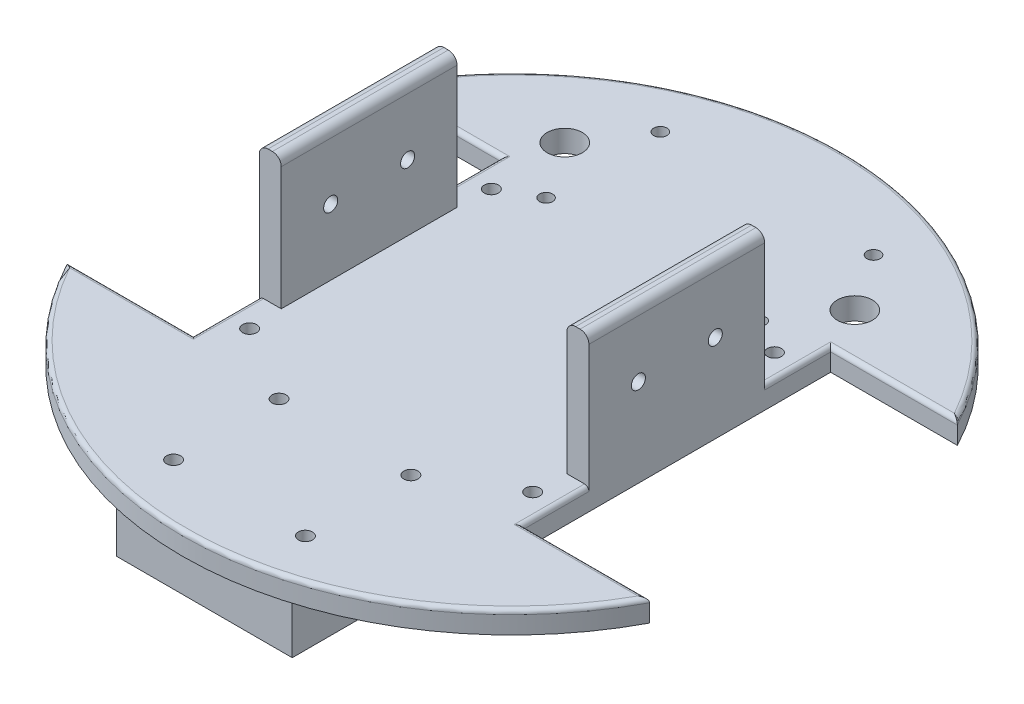
SolidWorks part; units mm, degrees
ref_plane "Front Plane" through (0, 0, 0) normal (0, 0, 1) x (1, 0, 0)
ref_plane "Top Plane" through (0, 0, 0) normal (0, 1, 0) x (1, 0, 0)
ref_plane "Right Plane" through (0, 0, 0) normal (1, 0, 0) x (0, 0, -1)
sketch "Sketch1" plane through (0, 0, 0) normal (0, 1, 0) x (1, 0, 0)
  circle A0 centre (0, 0) radius 75
  dimension "D1" = 150
extrude "Boss-Extrude2" add sketch "Sketch1" along normal blind 5 contours A0
sketch "Sketch5" plane through (0, 5, 0) normal (0, 1, 0) x (1, 0, 0)
  line L0 (0, 0) -> (162.2631, 0) construction
  line L1 (0, 0) -> (0, 110.711) construction
  line L2 (37.5, 35) -> (72.5, 35)
  line L3 (37.5, 35) -> (37.5, -35)
  line L4 (37.5, -35) -> (72.5, -35)
  line L5 (72.5, 35) -> (72.5, -35)
  line L6 (37.5, 35) -> (72.5, -35) construction
  line L7 (37.5, -35) -> (72.5, 35) construction
  line L8 (-72.5, 35) -> (-72.5, -35)
  line L9 (-37.5, -35) -> (-72.5, -35)
  line L10 (-37.5, 35) -> (-37.5, -35)
  line L11 (-37.5, 35) -> (-72.5, 35)
  point P3 (55, 0)
  dimension "D1" = 70
  dimension "D2" = 35
  dimension "D3" = 55
extrude "Cut-Extrude1" cut sketch "Sketch5" against normal through all
sketch "Sketch6" plane through (0, 5, 0) normal (0, 1, 0) x (1, 0, 0)
  line L0 (-37.5, -35) -> (-37.5, 35) construction
  line L1 (-37.5, 20) -> (-32.5, 20)
  line L2 (-37.5, 20) -> (-37.5, -20)
  line L3 (-37.5, -20) -> (-32.5, -20)
  line L4 (-32.5, 20) -> (-32.5, -20)
  point P4 (-37.5, 0)
  dimension "D1" = 5
  dimension "D2" = 40
extrude "Boss-Extrude3" add sketch "Sketch6" along normal blind 30
sketch "Sketch7" plane through (-32.5, 0, 0) normal (1, 0, 0) x (0, 0, -1)
  line L0 (-20, 35) -> (-20, 5) construction
  line L1 (-20, 5) -> (20, 5) construction
  circle A0 centre (-8.75, 20) radius 1.6
  circle A1 centre (8.75, 20) radius 1.6
  dimension "D1" = 3.2
  dimension "D2" = 3.2
  dimension "D3" = 17.5
  dimension "D4" = 15
  dimension "D5" = 11.25
extrude "Cut-Extrude2" cut sketch "Sketch7" against normal through all
mirror "Mirror1" about plane through (0, 0, 0) normal (1, 0, 0) of "Boss-Extrude3", "Cut-Extrude2"
delete or keep bodies "Body-Delete/Keep 1" type delete bodies bodies 104
delete or keep bodies "Body-Delete/Keep 2" type delete bodies bodies 105
sketch "Sketch8" plane through (0, 0, 0) normal (0, -1, 0) x (1, 0, 0)
  line L1 (-20, 70) -> (20, 70)
  line L2 (-20, 70) -> (-20, 30)
  line L3 (-20, 30) -> (20, 30)
  line L4 (20, 70) -> (20, 30)
  line L5 (-20, 70) -> (20, 30) construction
  line L6 (-20, 30) -> (20, 70) construction
  point P0 (0, 50)
  dimension "D1" = 40
  dimension "D2" = 40
  dimension "D3" = 50
extrude "Boss-Extrude5" add sketch "Sketch8" along normal blind 12.5
sketch "Sketch9" plane through (0, -12.5, 0) normal (0, -1, 0) x (1, 0, 0)
  line L1 (-20, 70) -> (-20, 30) construction
  line L3 (20, 70) -> (-20, 70) construction
  circle A0 centre (-15, 62) radius 1.6
  circle A1 centre (15, 62) radius 1.6
  circle A2 centre (-15, 38) radius 1.6
  circle A3 centre (15, 38) radius 1.6
  dimension "D1" = 3.2
  dimension "D2" = 3.2
  dimension "D3" = 3.2
  dimension "D4" = 3.2
  dimension "D5" = 30
  dimension "D6" = 30
  dimension "D7" = 24
  dimension "D8" = 5
  dimension "D9" = 8
extrude "Cut-Extrude3" cut sketch "Sketch9" against normal through all
sketch "Sketch10" plane through (0, 5, 0) normal (0, 1, 0) x (1, 0, 0)
  line L1 (-32.2, 27.5) -> (32.2, 27.5) construction
  line L2 (-32.2, 27.5) -> (-32.2, -27.5) construction
  line L3 (-32.2, -27.5) -> (32.2, -27.5) construction
  line L4 (32.2, 27.5) -> (32.2, -27.5) construction
  line L5 (-32.2, 27.5) -> (32.2, -27.5) construction
  line L6 (-32.2, -27.5) -> (32.2, 27.5) construction
  circle A0 centre (32.2, 27.5) radius 1.6
  circle A1 centre (-32.2, 27.5) radius 1.6
  circle A2 centre (-32.2, -27.5) radius 1.6
  circle A3 centre (32.2, -27.5) radius 1.6
  circle A4 centre (-33, 45) radius 4
  circle A5 centre (33, 45) radius 4
  point P0 (0, 0)
  dimension "D3" = 3.2
  dimension "D4" = 3.2
  dimension "D5" = 3.2
  dimension "D6" = 3.2
  dimension "D9" = 33
  dimension "D10" = 33
  dimension "D11" = 45
  dimension "D7" = 8
  dimension "D8" = 8
  dimension "D2" = 55
  dimension "D12" = 64.4
extrude "Cut-Extrude8" cut sketch "Sketch10" against normal through all
sketch "Sketch13" plane through (0, 5, 0) normal (0, 1, 0) x (1, 0, 0)
  line L1 (-24.25, 58) -> (24.25, 58)
  line L2 (-24.25, 58) -> (-24.25, 32)
  line L3 (-24.25, 32) -> (24.25, 32)
  line L4 (24.25, 58) -> (24.25, 32)
  line L5 (-24.25, 58) -> (24.25, 32) construction
  line L6 (-24.25, 32) -> (24.25, 58) construction
  circle A0 centre (24.25, 58) radius 1.5
  circle A1 centre (-24.25, 58) radius 1.5
  circle A2 centre (-24.25, 32) radius 1.5
  circle A3 centre (24.25, 32) radius 1.5
  point P0 (0, 45)
  dimension "D3" = 3
  dimension "D4" = 3
  dimension "D5" = 3
  dimension "D6" = 3
  dimension "D1" = 48.5
  dimension "D2" = 26
  dimension "D7" = 45
extrude "Cut-Extrude9" cut sketch "Sketch13" against normal through all contours A1 | A0 | A3 | A2
fillet "Fillet1" radius 1 10 edges at (51.9162, 5, -35) (37.5, 5, -27.5) (37.5, 5, 27.5) (51.9162, 5, 35) (0, 5, 75) (-51.9162, 5, 35) (-37.5, 5, 27.5) (-37.5, 5, -27.5) (-51.9162, 5, -35) (0, 5, -75)
fillet "Fillet2" radius 2 4 edges at (37.5, 35, 0) (32.5, 35, 0) (-37.5, 35, 0) (-32.5, 35, 0)
